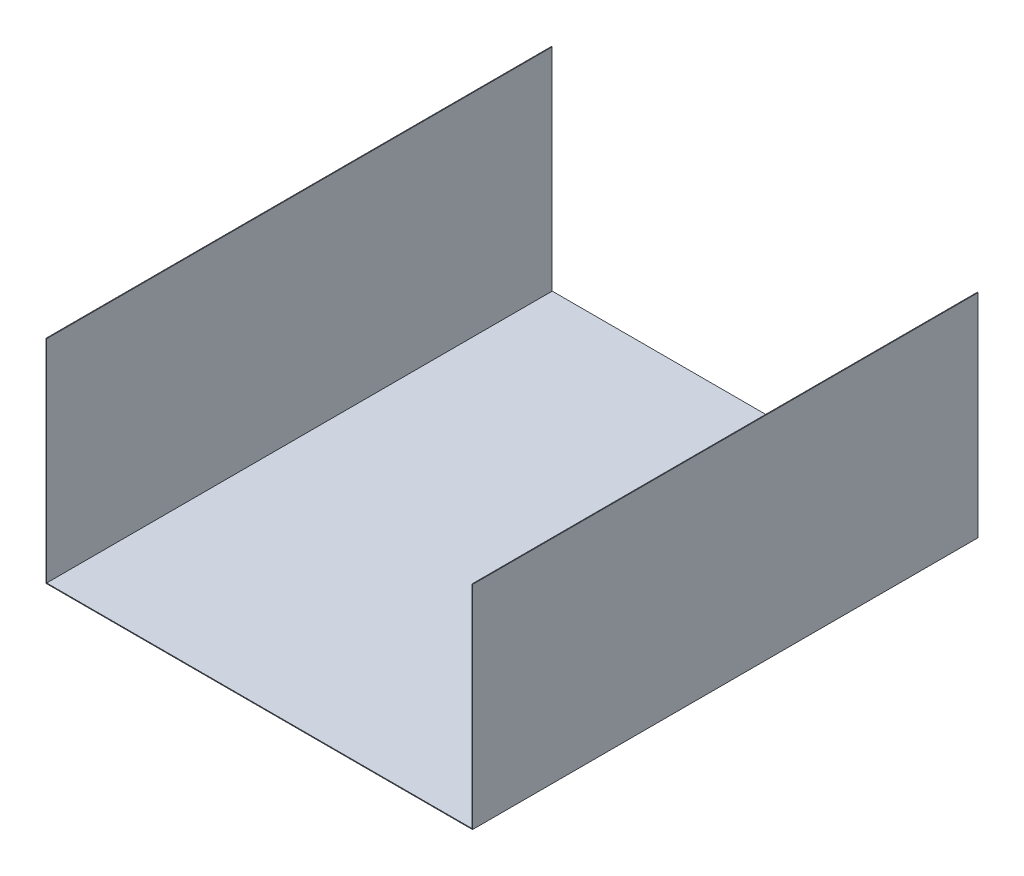
SolidWorks part; units mm, degrees
ref_plane "Front Plane" through (0, 0, 0) normal (0, 0, 1) x (1, 0, 0)
ref_plane "Top Plane" through (0, 0, 0) normal (0, 1, 0) x (1, 0, 0)
ref_plane "Right Plane" through (0, 0, 0) normal (1, 0, 0) x (0, 0, -1)
other "Configuration Table"
sketch "Sketch1" plane through (0, 0, 0) normal (0, 0, 1) x (1, 0, 0)
  line L0 (13.7, 298) -> (13.7, 4)
  line L1 (13.7, 4) -> (604.3, 4)
  line L2 (604.3, 4) -> (604.3, 298)
  line L3 (604.3, 298) -> (603.3, 298)
  line L4 (603.3, 298) -> (603.3, 5)
  line L5 (603.3, 5) -> (14.7, 5)
  line L6 (14.7, 5) -> (14.7, 298)
  line L7 (14.7, 298) -> (13.7, 298)
extrude "CEK_1L_kutu_U_1.0_1" add sketch "Sketch1" against normal blind 700 separate body
